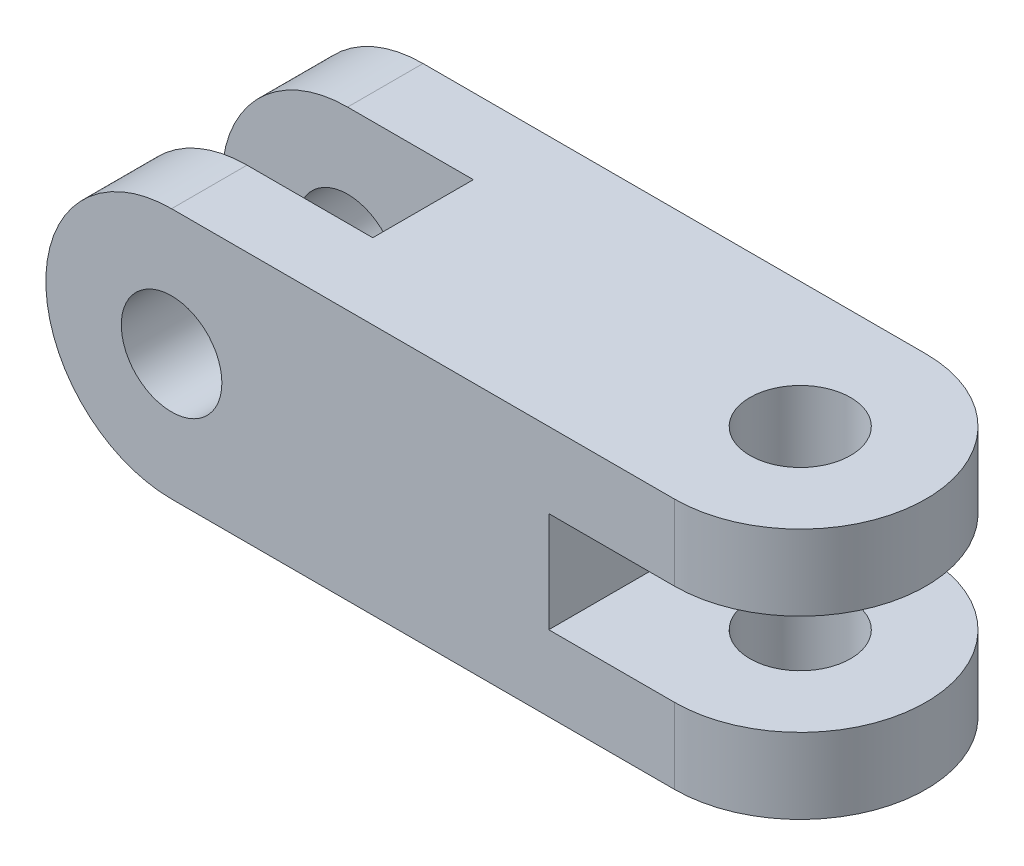
SolidWorks part; units mm, degrees
ref_plane "Front Plane" through (0, 0, 0) normal (0, 0, 1) x (1, 0, 0)
ref_plane "Top Plane" through (0, 0, 0) normal (0, 1, 0) x (1, 0, 0)
ref_plane "Right Plane" through (0, 0, 0) normal (1, 0, 0) x (0, 0, -1)
sketch "Sketch1" plane through (0, 0, 0) normal (0, 0, 1) x (1, 0, 0)
  line L0 (12.5, 10) -> (62.5, 10)
  line L1 (-62.5, 25) -> (62.5, 25)
  line L3 (-62.5, -25) -> (62.5, -25)
  line L4 (62.5, 25) -> (62.5, 10)
  line L5 (12.5, -10) -> (62.5, -10)
  line L6 (12.5, 10) -> (12.5, -10)
  line L7 (62.5, -10) -> (62.5, -25)
  line L8 (-62.5, 10) -> (62.5, 10) construction
  line L9 (12.5, 25) -> (12.5, -25) construction
  line L10 (-62.5, -10) -> (62.5, -10) construction
  line L12 (62.5, 25) -> (62.5, -25) construction
  arc A0 (-62.5, 25) -> (-62.5, -25) centre (-62.5, 0) ccw
  circle A1 centre (-62.5, 0) radius 10
  dimension "D6" = 50
  dimension "D7" = 20
  dimension "D1" = 125
  dimension "D2" = 50
extrude "Boss-Extrude1" add sketch "Sketch1" against normal blind 50
sketch "Sketch2" plane through (0, 25, 0) normal (0, 1, 0) x (1, 0, 0)
  line L3 (37.5, 50) -> (62.5, 50)
  line L4 (62.5, 50) -> (62.5, 25)
  arc A0 (62.5, 25) -> (37.5, 50) centre (37.5, 25) ccw
  dimension "D1" = 25
extrude "Cut-Extrude6" cut sketch "Sketch2" against normal blind 86 contours A0 L3 L4
sketch "Sketch3" plane through (0, 25, 0) normal (0, 1, 0) x (1, 0, 0)
  line L0 (37.5, 0) -> (62.5, 0)
  line L1 (62.5, 0) -> (62.5, 25)
  arc A0 (37.5, 0) -> (62.5, 25) centre (37.5, 25) ccw
extrude "Cut-Extrude7" cut sketch "Sketch3" against normal blind 86
sketch "Sketch4" plane through (0, 25, 0) normal (0, 1, 0) x (1, 0, 0)
  circle A0 centre (37.5, 25) radius 10
  dimension "D1" = 20
extrude "Cut-Extrude8" cut sketch "Sketch4" against normal blind 86
sketch "Sketch5" plane through (0, 25, 0) normal (0, 1, 0) x (1, 0, 0)
  line L0 (-62.5, 50) -> (-62.5, 0) construction
  line L1 (-37.5, 15) -> (-87.5, 15)
  line L2 (-37.5, 15) -> (-37.5, 35)
  line L3 (-37.5, 35) -> (-87.5, 35)
  line L4 (-87.5, 15) -> (-87.5, 35)
  line L5 (37.5, 50) -> (-62.5, 50) construction
  line L6 (37.5, 0) -> (-62.5, 0) construction
  line L7 (-87.5, 50) -> (-87.5, 0) construction
  point P0 (-62.5, 25)
  dimension "D1" = 50
  dimension "D2" = 15
  dimension "D3" = 15
extrude "Cut-Extrude9" cut sketch "Sketch5" against normal blind 86
